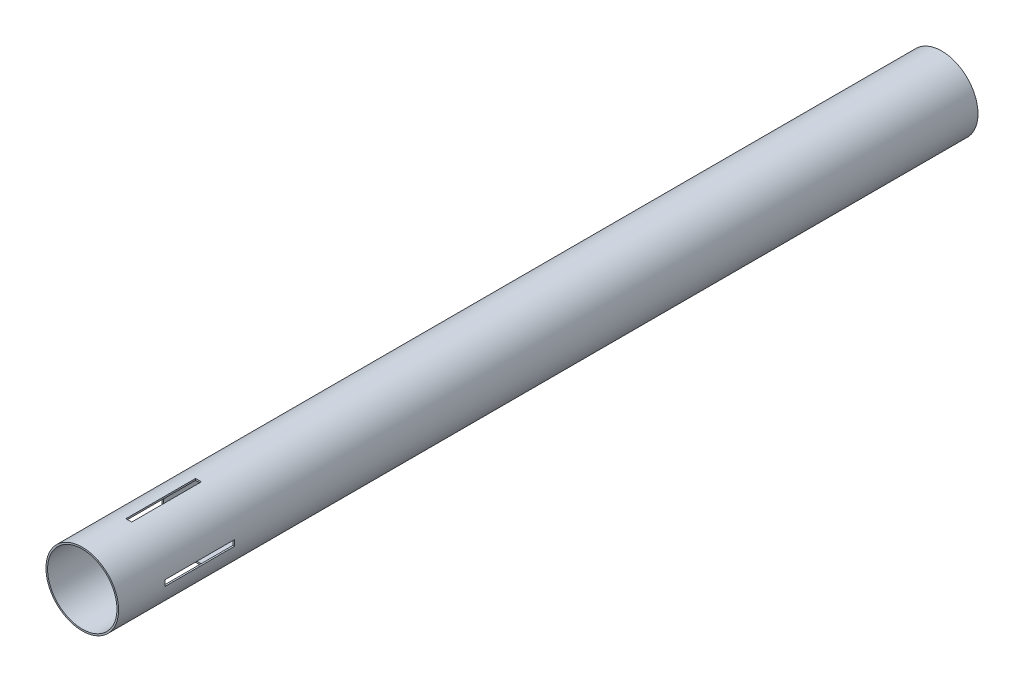
SolidWorks part; units mm, degrees
ref_plane "Front Plane" through (0, 0, 0) normal (0, 0, 1) x (1, 0, 0)
ref_plane "Top Plane" through (0, 0, 0) normal (0, 1, 0) x (1, 0, 0)
ref_plane "Right Plane" through (0, 0, 0) normal (1, 0, 0) x (0, 0, -1)
sketch "Sketch1" plane through (0, 0, 0) normal (0, 0, 1) x (1, 0, 0)
  circle A0 centre (0, 0) radius 37.9603
  circle A1 centre (0, 0) radius 39.7129
  dimension "D1" = 1.7526
  dimension "D2" = 75.9206
extrude "Boss-Extrude1" add sketch "Sketch1" along normal blind 939.8
sketch "Sketch3" plane through (0, 0, 0) normal (0, 1, 0) x (1, 0, 0)
  line L0 (-3.175, -889) -> (-3.175, -812.8)
  line L1 (-3.175, -812.8) -> (3.175, -812.8)
  line L2 (3.175, -812.8) -> (3.175, -889)
  line L3 (3.175, -889) -> (-3.175, -889)
  point P6 (0, -889)
  dimension "D1" = 76.2
  dimension "D2" = 6.35
  dimension "D3" = 50.8
sketch "Sketch4" plane through (0, 0, 0) normal (1, 0, 0) x (0, 0, -1)
  line L0 (-889, 3.175) -> (-812.8, 3.175)
  line L1 (-812.8, 3.175) -> (-812.8, -3.175)
  line L2 (-812.8, -3.175) -> (-889, -3.175)
  line L3 (-889, -3.175) -> (-889, 3.175)
  line L4 (-939.8, 39.7129) -> (-939.8, -39.7129) construction
  line L5 (-939.8, 0) -> (0, 0) construction
  point P6 (-812.8, 0)
  dimension "D1" = 50.8
  dimension "D2" = 76.2
  dimension "D3" = 6.35
extrude "Cut-Extrude1" cut sketch "Sketch3" against normal through all both and the other way through all
extrude "Cut-Extrude2" cut sketch "Sketch4" against normal through all both and the other way through all contours L2 L3 L0 L1
